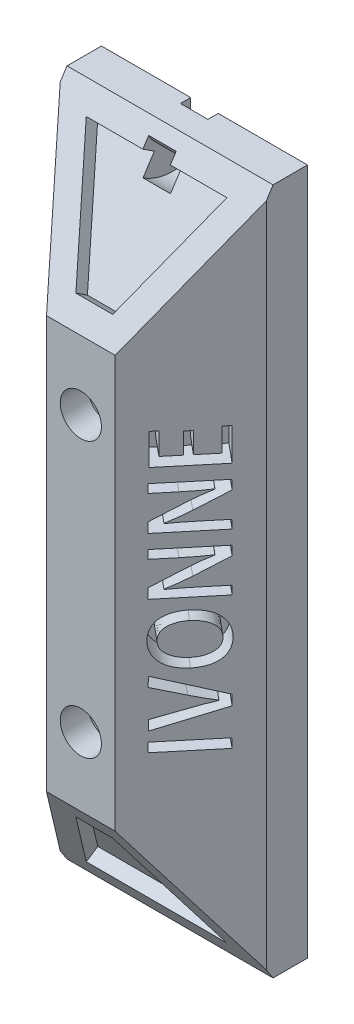
SolidWorks part; units mm, degrees
ref_plane "Alzado" through (0, 0, 0) normal (0, 0, 1) x (1, 0, 0)
ref_plane "Planta" through (0, 0, 0) normal (0, 1, 0) x (1, 0, 0)
ref_plane "Vista lateral" through (0, 0, 0) normal (1, 0, 0) x (0, 0, -1)
sketch "Croquis1" plane through (0, 0, 0) normal (0, 0, 1) x (1, 0, 0)
  line L0 (-7.5, 0) -> (7.5, 0)
  line L1 (7.5, 0) -> (7.5, 3)
  line L2 (7.5, 3) -> (2.5, 9)
  line L3 (2.5, 9) -> (-2.5, 9)
  line L4 (-2.5, 9) -> (-7.5, 3)
  line L5 (-7.5, 3) -> (-7.5, 0)
  line L6 (0, 0) -> (0, 9) construction
  point P4 (0, 0)
  dimension "D1" = 15
  dimension "D2" = 9
  dimension "D3" = 5
  dimension "D4" = 3
extrude "Saliente-Extruir1" add sketch "Croquis1" along normal blind 50
chamfer "Chaflán1" distance 10 angle 33 2 edges at (0, 9, 0) (0, 9, 50)
sketch "Croquis3" plane through (0, 24.6012, 15.9762) normal (0, 0.8387, 0.5446) x (1, 0, 0)
  line L0 (0, -28.6451) -> (0, -40.5687) construction
  line L1 (-2.5, -28.6451) -> (2.5, -28.6451) construction
  line L2 (7.5, -40.5687) -> (-7.5, -40.5687) construction
  line L3 (-5.1181, -38.7687) -> (5.1181, -38.7687)
  line L4 (5.1181, -38.7687) -> (1.3402, -30.4451)
  line L5 (1.3402, -30.4451) -> (-1.3402, -30.4451)
  line L6 (-1.3402, -30.4451) -> (-5.1181, -38.7687)
  line L7 (-7.5, -39.6615) -> (-2.5, -28.6451) construction
  line L8 (2.5, -28.6451) -> (7.5, -39.6615) construction
  line L9 (-3.2291, -34.6069) -> (-4.8682, -33.863) construction
  line L10 (1.0689, -30.4451) -> (1.0689, -28.6451) construction
  line L11 (-1.937, -38.7687) -> (-1.937, -40.5687) construction
  point P9 (0, -38.7687)
  dimension "D1" = 1.8
  dimension "D2" = 2.6805
extrude "Cortar-Extruir1" cut sketch "Croquis3" against normal blind 1
ref_plane "Plano1" through (0, 0, 25) normal (0, 0, 1) x (1, 0, 0)
mirror "Simetría1" about plane through (0, 0, 25) normal (0, 0, 1) of "Cortar-Extruir1"
sketch "Croquis4" plane through (0, 9, 0) normal (0, 1, 0) x (1, 0, 0)
  line L0 (-2.5, -25) -> (2.5, -25) construction
  line L1 (-2.5, -40) -> (-2.5, -10) construction
  line L2 (2.5, -40) -> (2.5, -10) construction
  line L3 (0, -35) -> (0, -15)
  circle A0 centre (0, -35) radius 1.5
  circle A1 centre (0, -15) radius 1.5
  point P10 (0, -25)
  dimension "D1" = 3
  dimension "D2" = 20
extrude "Huecos tornillos" cut sketch "Croquis4" against normal blind 2
sketch "Croquis5" plane through (5.9016, 4.918, 0) normal (0.7682, 0.6402, 0) x (0, 0, -1)
  line L0 (-44.6196, -0.7331) -> (-5.3804, -0.7331) construction
  line L3 (-49.2392, -2.4967) -> (-0.7608, -2.4967) construction
  text T0 "IVONNE" font "@Adobe Heiti Std R" height in points 14
extrude "PUEBLA-1" cut sketch "Croquis5" against normal blind 1.8
sketch "Croquis7" plane through (-5.9016, 4.918, 0) normal (-0.7682, 0.6402, 0) x (0, 0, 1)
  line L0 (5.3804, -0.7404) -> (44.6196, -0.7404) construction
  text T0 "PUEBLA" font "@Adobe Heiti Std R" height in points 14
extrude "PUEBLA-2" cut sketch "Croquis7" against normal blind 1.8
sketch "Croquis8" plane through (7.5, 0, 0) normal (1, 0, 0) x (0, 0, -1)
  line L0 (0, 0) -> (0, 2.5059) construction
  circle A0 centre (0, 1.253) radius 2
  circle A1 centre (0, 1.253) radius 4
  dimension "D1" = 2
  dimension "D2" = 4
extrude "ranura llavero" cut sketch "Croquis8" against normal blind 1 and the other way blind 1 from offset 7.5 offset against normal yes
sketch "Croquis10" plane through (0, 0, 0) normal (0, -1, 0) x (1, 0, 0)
  line L0 (-1, 2) -> (-1, 0)
  line L1 (-7.5, 0) -> (7.5, 0) construction
  line L2 (-1, 0) -> (1, 0)
  line L3 (1, 0) -> (1, 2)
  line L4 (1, 2) -> (-1, 2)
  line L5 (1, 2) -> (-1, 2) construction
extrude "espacio llavero debajo" cut sketch "Croquis10" against normal blind 0.75
sketch "Croquis23" [suppressed] plane through (0, 0, 0) normal (0, -1, 0) x (1, 0, 0)
  line L9 (-4.8602, 5.453) -> (-4.533, 5.1217)
  line L88 (-4.0291, 5.2989) -> (-4.0291, 5.7833)
  line L89 (-4.0291, 5.7833) -> (0.1999, 5.7833)
  line L90 (4.523, 6.259) -> (4.5043, 6.6454)
  line L91 (4.5043, 6.6454) -> (-0.1776, 6.6613)
  line L92 (-0.1776, 6.6613) -> (-4.8602, 6.6773)
  line L93 (-4.8602, 6.6773) -> (-4.8602, 6.0616)
  line L94 (-4.8602, 6.0616) -> (-4.8602, 5.453)
  line L95 (-4.8602, 5.453) -> (-4.8602, 5.453)
  line L96 (-4.836, 5.4629) -> (-4.836, 5.463)
  line L97 (-4.674, 23.8444) -> (-0.8024, 23.8444)
  line L109 (4.5212, 25.4088) -> (4.5043, 25.7617)
  line L188 (4.5043, 25.7617) -> (4.1218, 25.7617)
  line L189 (4.1218, 25.7617) -> (3.7406, 25.7617)
  line L190 (3.7406, 25.7617) -> (3.687, 25.4418)
  line L191 (0.4454, 24.6873) -> (-2.1005, 24.666)
  line L192 (-2.1005, 24.666) -> (-2.1181, 25.2021)
  line L193 (-2.1181, 25.2021) -> (-2.1365, 25.7617)
  line L194 (-2.1365, 25.7617) -> (-2.5517, 25.7617)
  line L195 (-2.5517, 25.7617) -> (-2.9668, 25.7617)
  line L200 (-2.9668, 25.7617) -> (-2.9851, 25.2069)
  line L201 (-2.9851, 25.2069) -> (-3.0027, 24.6755)
  line L202 (-3.0027, 24.6755) -> (-3.8264, 24.6755)
  line L203 (-3.8264, 24.6755) -> (-4.674, 24.6755)
  line L204 (-4.674, 24.6755) -> (-4.674, 24.26)
  line L205 (-4.674, 24.26) -> (-4.674, 23.8444)
  line L206 (-4.674, 30.3613) -> (-0.7631, 30.3613)
  line L207 (4.5296, 31.9094) -> (4.5361, 32.2475)
  line L208 (4.5361, 32.2475) -> (4.1284, 32.2475)
  line L209 (4.1284, 32.2475) -> (3.7223, 32.2475)
  line L210 (3.7223, 32.2475) -> (3.6813, 31.9377)
  line L211 (0.4739, 31.2054) -> (-2.1051, 31.1851)
  line L212 (-2.1051, 31.1851) -> (-2.1051, 31.7042)
  line L213 (-2.9983, 31.6692) -> (-2.9983, 31.1924)
  line L214 (-2.9983, 31.1924) -> (-3.824, 31.1924)
  line L215 (-3.824, 31.1924) -> (-4.674, 31.1924)
  line L216 (-4.674, 31.1924) -> (-4.674, 30.7592)
  line L217 (-4.674, 30.7592) -> (-4.674, 30.3613)
  line L218 (4.4171, 16.1181) -> (4.4283, 16.1365)
  line L219 (4.4283, 16.1365) -> (4.4261, 16.1365)
  line L220 (4.5314, 16.5641) -> (4.5272, 16.8123)
  line L221 (4.5272, 16.8123) -> (4.5346, 17.067)
  line L222 (2.6505, 18.7792) -> (2.2153, 18.7792)
  line L223 (2.2153, 18.7792) -> (2.2153, 18.3723)
  line L224 (2.2153, 18.3723) -> (2.2153, 17.9665)
  line L225 (2.2153, 17.9665) -> (2.6451, 17.9231)
  line L226 (2.3822, 16.1838) -> (1.7072, 16.1616)
  line L227 (1.7072, 16.1616) -> (1.0601, 17.4636)
  line L228 (1.0601, 17.4636) -> (0.4063, 18.7792)
  line L229 (0.4063, 18.7792) -> (-0.5423, 18.7792)
  line L230 (4.5312, 38.1525) -> (4.5317, 38.8949)
  line L231 (2.7866, 40.1384) -> (2.3089, 40.1615)
  line L232 (2.3089, 40.1615) -> (2.29, 39.7304)
  line L233 (2.29, 39.7304) -> (2.2711, 39.2988)
  line L234 (2.2711, 39.2988) -> (2.5008, 39.2988)
  line L235 (-1.1845, 39.2674) -> (-0.7092, 39.3356)
  line L236 (-0.7092, 39.3356) -> (-0.6904, 39.7237)
  line L237 (4.5296, 42.0359) -> (4.5305, 42.6933)
  line L238 (4.5305, 42.6933) -> (4.5332, 42.8981)
  line L239 (4.4549, 44.1716) -> (4.4547, 44.1716)
  line L240 (4.4547, 44.1716) -> (4.4546, 44.1716)
  line L241 (4.4546, 44.1716) -> (-1.4639, 44.172)
  line L242 (-1.4639, 44.172) -> (-1.5989, 44.17)
  line L243 (4.5359, 8.1299) -> (4.5359, 8.5506)
  line L244 (4.5359, 8.5506) -> (1.5603, 8.5506)
  line L245 (1.5138, 10.3141) -> (4.5044, 10.3453)
  line L246 (4.5044, 10.3453) -> (4.5233, 10.7789)
  line L247 (4.5233, 10.7789) -> (4.5423, 11.2138)
  line L248 (4.5423, 11.2138) -> (1.4389, 11.195)
  line L249 (4.5359, 19.9855) -> (4.5359, 20.3884)
  line L250 (4.5359, 20.3884) -> (1.5603, 20.4062)
  line L251 (1.532, 22.156) -> (4.542, 22.1744)
  line L252 (4.542, 22.1744) -> (4.5232, 22.6031)
  line L253 (4.5232, 22.6031) -> (4.5044, 23.0307)
  line L254 (4.5044, 23.0307) -> (1.731, 23.0478)
  line L255 (4.5336, 33.8803) -> (4.5319, 34.1285)
  line L256 (4.5319, 34.5628) -> (4.5339, 34.7986)
  line L257 (2.7711, 36.0835) -> (2.2153, 36.1114)
  line L258 (2.2153, 36.1114) -> (2.2153, 35.7)
  line L259 (2.2153, 35.7) -> (2.2153, 35.2909)
  line L260 (2.2153, 35.2909) -> (2.6777, 35.2243)
  line L261 (2.2806, 33.4892) -> (1.6897, 33.4888)
  line L262 (1.6897, 33.4888) -> (1.0517, 34.7913)
  line L263 (1.0517, 34.7913) -> (0.407, 36.1075)
  line L264 (0.407, 36.1075) -> (-0.6574, 36.0846)
  line L265 (4.4622, 26.985) -> (4.4721, 27.003)
  line L266 (4.4721, 27.003) -> (4.4692, 27.003)
  line L267 (4.5297, 27.3634) -> (4.5273, 27.6117)
  line L268 (4.5117, 20.3643) -> (4.5117, 19.9855)
  line L269 (-3.0334, 21.2807) -> (-3.0334, 21.2808)
  line L270 (4.2314, 12.8087) -> (4.5359, 12.8713)
  line L271 (4.5359, 12.8713) -> (4.5359, 13.2433)
  line L272 (4.5359, 13.2433) -> (4.5359, 13.6152)
  line L273 (4.5359, 13.6152) -> (4.2315, 13.6803)
  line L274 (-2.9983, 11.8993) -> (-2.9983, 11.8993)
  line L275 (-2.9741, 11.8994) -> (-2.9741, 11.8993)
  line L276 (-0.4884, 35.2633) -> (-0.2015, 35.2645)
  line L277 (-0.2015, 35.2645) -> (0.2301, 34.4032)
  line L278 (-0.5815, 17.9469) -> (-0.2015, 17.9482)
  line L279 (-0.2015, 17.9482) -> (0.2301, 17.0868)
  spline S0 degree 3 poles (-4.533, 5.1217) (-4.5035, 5.0924) (-4.4466, 5.0359) (-4.3621, 4.9585) (-4.2952, 4.9011) (-4.2461, 4.8622) (-4.2142, 4.8383) (-4.1858, 4.819) (-4.1616, 4.8039) (-4.1409, 4.7933) (-4.121, 4.7889) (-4.1018, 4.7931) (-4.0852, 4.8052) (-4.072, 4.8236) (-4.0618, 4.8479) (-4.0534, 4.878) (-4.0434, 4.9319) (-4.0351, 5.0186) (-4.0298, 5.1475) (-4.0294, 5.2446) (-4.0291, 5.2989) knots 0 0 0 0 0.115946 0.224108 0.320001 0.361964 0.399248 0.431375 0.457779 0.478836 0.49618 0.513638 0.53192 0.552362 0.57622 0.605016 0.63966 0.729037 0.848151 1 1 1 1
  spline S1 degree 3 poles (0.1999, 5.7833) (0.5752, 5.7836) (1.2893, 5.7842) (2.2921, 5.7885) (3.0408, 5.7942) (3.554, 5.8) (3.8624, 5.8046) (4.0838, 5.8089) (4.2304, 5.8127) (4.3159, 5.8154) (4.3766, 5.8178) (4.4164, 5.8198) (4.4395, 5.8213) (4.456, 5.8225) (4.4669, 5.8236) (4.4735, 5.8244) (4.4782, 5.8251) (4.4816, 5.8256) (4.4838, 5.8261) (4.4859, 5.8267) (4.4881, 5.8271) (4.4909, 5.8283) (4.4946, 5.8316) (4.4987, 5.8369) (4.5023, 5.8442) (4.5052, 5.8525) (4.508, 5.8619) (4.5105, 5.8725) (4.5137, 5.8891) (4.5171, 5.913) (4.5205, 5.945) (4.5242, 5.9955) (4.5267, 6.0669) (4.5269, 6.16) (4.5243, 6.2252) (4.523, 6.259) knots 0 0 0 0 0.238071 0.453081 0.636227 0.713099 0.778704 0.831946 0.853588 0.871732 0.886247 0.892105 0.897014 0.900968 0.902584 0.903969 0.905139 0.905647 0.906119 0.906572 0.907018 0.907574 0.908473 0.910111 0.911781 0.913613 0.915677 0.917986 0.920548 0.926427 0.933254 0.940954 0.958598 0.978554 1 1 1 1
  spline S2 degree 3 poles (-0.8024, 23.8444) (0.0364, 23.845) (1.2812, 23.8458) (2.6838, 23.8589) (3.3332, 23.9062) (3.6318, 24.0192) (3.8297, 24.1167) (4.0103, 24.2298) (4.1539, 24.3836) (4.2826, 24.5543) (4.3964, 24.751) (4.4791, 24.9573) (4.5261, 25.1817) (4.5229, 25.3309) (4.5212, 25.4088) knots 0 0 0 0 0.404979 0.601004 0.68012 0.716413 0.754468 0.786796 0.818638 0.855447 0.890061 0.928098 0.96245 1 1 1 1
  spline S3 degree 3 poles (3.687, 25.4418) (3.6816, 25.4132) (3.6707, 25.3557) (3.6478, 25.2719) (3.6218, 25.1926) (3.5934, 25.1222) (3.5653, 25.0647) (3.5236, 25.003) (3.4448, 24.942) (3.339, 24.8707) (3.1644, 24.7708) (2.735, 24.7213) (1.8158, 24.7009) (0.9952, 24.6927) (0.4454, 24.6873) knots 0 0 0 0 0.024157 0.048552 0.07202 0.093418 0.111517 0.125098 0.154806 0.193069 0.231545 0.320142 0.544436 1 1 1 1
  spline S4 degree 3 poles (-0.7631, 30.3613) (0.0842, 30.3625) (1.3391, 30.3642) (2.7501, 30.3736) (3.4028, 30.4249) (3.7044, 30.5394) (3.9156, 30.6737) (4.0957, 30.8424) (4.2538, 31.0255) (4.3736, 31.1956) (4.461, 31.359) (4.4933, 31.5323) (4.5202, 31.7137) (4.5264, 31.8444) (4.5296, 31.9094) knots 0 0 0 0 0.411894 0.610137 0.688322 0.727681 0.765748 0.809404 0.847223 0.883282 0.91065 0.936429 0.968386 1 1 1 1
  spline S5 degree 3 poles (3.6813, 31.9377) (3.6706, 31.8803) (3.6498, 31.769) (3.5941, 31.6229) (3.5229, 31.5045) (3.4263, 31.4234) (3.3292, 31.3548) (3.2486, 31.3019) (3.1737, 31.283) (3.0996, 31.2733) (2.993, 31.2629) (2.8535, 31.2538) (2.6805, 31.2452) (2.3804, 31.234) (1.9152, 31.2226) (1.2449, 31.2122) (0.748, 31.2078) (0.4739, 31.2054) knots 0 0 0 0 0.048816 0.094618 0.130448 0.1631 0.199111 0.230695 0.242519 0.263434 0.293324 0.332245 0.380521 0.438382 0.583791 0.770368 1 1 1 1
  spline S6 degree 3 poles (-2.1051, 31.7042) (-2.1054, 31.7614) (-2.1059, 31.8642) (-2.1112, 32.0015) (-2.1194, 32.0949) (-2.1292, 32.1535) (-2.1373, 32.1867) (-2.147, 32.2136) (-2.1591, 32.2343) (-2.1746, 32.2495) (-2.2133, 32.2593) (-2.2886, 32.2572) (-2.4076, 32.2657) (-2.5266, 32.2699) (-2.628, 32.2715) (-2.7021, 32.2682) (-2.7704, 32.2617) (-2.8299, 32.2528) (-2.8779, 32.2413) (-2.912, 32.2276) (-2.9319, 32.208) (-2.9441, 32.1868) (-2.9546, 32.1605) (-2.9639, 32.1286) (-2.972, 32.0911) (-2.9819, 32.0296) (-2.9909, 31.9382) (-2.9973, 31.8113) (-2.9979, 31.7191) (-2.9983, 31.6692) knots 0 0 0 0 0.091635 0.164427 0.219802 0.241473 0.259534 0.274426 0.286968 0.297829 0.307914 0.349599 0.41806 0.498792 0.540099 0.5802 0.617395 0.649878 0.676396 0.696464 0.707563 0.720297 0.735302 0.752916 0.773355 0.796731 0.852482 0.920263 1 1 1 1
  spline S7 degree 3 poles (-3.0603, 16.9878) (-3.0592, 16.8906) (-3.0571, 16.714) (-3.0034, 16.4571) (-2.9082, 16.2368) (-2.7861, 16.0339) (-2.646, 15.8615) (-2.4876, 15.7152) (-2.3031, 15.6034) (-2.112, 15.5035) (-1.928, 15.4235) (-1.7429, 15.371) (-1.5202, 15.3421) (-1.1955, 15.3246) (-0.7176, 15.3149) (-0.0355, 15.3107) (0.8099, 15.3103) (1.6577, 15.3106) (2.35, 15.3143) (2.8241, 15.3243) (3.1397, 15.3428) (3.3562, 15.3766) (3.5388, 15.4356) (3.7224, 15.5184) (3.9078, 15.6209) (4.0737, 15.7321) (4.2067, 15.86) (4.3236, 15.9848) (4.3879, 16.0764) (4.4171, 16.1181) knots 0 0 0 0 0.033474 0.060852 0.089936 0.115893 0.14239 0.166392 0.189902 0.216553 0.240885 0.259001 0.282767 0.318191 0.371217 0.447755 0.553655 0.663009 0.740387 0.792636 0.826675 0.849467 0.868016 0.892741 0.918872 0.941121 0.961395 0.982429 1 1 1 1
  spline S8 degree 3 poles (4.4261, 16.1365) (4.446, 16.1796) (4.4876, 16.2695) (4.5233, 16.4145) (4.5287, 16.5151) (4.5314, 16.5641) knots 0 0 0 0 0.319971 0.669084 1 1 1 1
  spline S9 degree 3 poles (4.5346, 17.067) (4.5257, 17.1146) (4.5132, 17.1814) (4.5534, 17.3232) (4.5282, 17.3196) (4.5274, 17.3195) knots 0 0 0 0 0.705879 0.991017 1 1 1 1
  spline S10 degree 3 poles (4.5274, 17.3195) (4.5283, 17.3218) (4.53, 17.3266) (4.5274, 17.3345) (4.5276, 17.3429) (4.5278, 17.3516) (4.5246, 17.3611) (4.5249, 17.3808) (4.527, 17.413) (4.5281, 17.46) (4.5313, 17.5541) (4.525, 17.6901) (4.4731, 17.861) (4.3851, 18.0164) (4.262, 18.1622) (4.122, 18.2971) (3.9642, 18.4237) (3.7818, 18.5253) (3.5898, 18.6149) (3.3853, 18.6937) (3.1574, 18.7384) (2.9109, 18.7706) (2.7363, 18.7764) (2.6505, 18.7792) knots 0 0 0 0 0.002681 0.00556 0.008912 0.012023 0.015169 0.019893 0.033833 0.051275 0.072316 0.138944 0.201935 0.269662 0.336675 0.414045 0.48641 0.561583 0.646172 0.722874 0.805208 0.904392 1 1 1 1
  spline S11 degree 3 poles (2.6451, 17.9231) (2.7272, 17.9118) (2.8918, 17.8891) (3.1169, 17.8325) (3.3122, 17.7682) (3.4641, 17.6753) (3.5856, 17.5802) (3.6871, 17.4779) (3.7402, 17.3474) (3.7778, 17.2063) (3.7974, 17.0489) (3.7871, 16.8931) (3.7473, 16.7462) (3.6775, 16.6182) (3.5705, 16.5102) (3.4468, 16.4118) (3.2909, 16.3131) (3.0777, 16.2384) (2.7659, 16.1986) (2.5258, 16.1893) (2.3822, 16.1838) knots 0 0 0 0 0.071677 0.143744 0.200762 0.248843 0.296831 0.3347 0.371627 0.416944 0.461259 0.508217 0.551219 0.592125 0.632837 0.681882 0.728922 0.791897 0.875562 1 1 1 1
  spline S12 degree 3 poles (-0.5423, 18.7792) (-0.7496, 18.7789) (-1.0929, 18.7784) (-1.5515, 18.7454) (-1.8915, 18.6584) (-2.1752, 18.5603) (-2.4174, 18.4174) (-2.6114, 18.2394) (-2.7798, 18.0496) (-2.9052, 17.8654) (-2.9928, 17.6787) (-3.027, 17.4694) (-3.0539, 17.2394) (-3.0582, 17.0721) (-3.0603, 16.9878) knots 0 0 0 0 0.174123 0.288318 0.384596 0.467994 0.539585 0.618857 0.688095 0.752242 0.805463 0.859622 0.92923 1 1 1 1
  spline S13 degree 3 poles (-3.0603, 38.4494) (-3.059, 38.3492) (-3.0566, 38.1697) (-3.0154, 37.9199) (-2.9392, 37.716) (-2.8282, 37.5373) (-2.7018, 37.377) (-2.5565, 37.2253) (-2.379, 37.1024) (-2.1875, 36.9935) (-2.0009, 36.9088) (-1.8151, 36.8547) (-1.5986, 36.8226) (-1.2902, 36.8016) (-0.8432, 36.787) (-0.2106, 36.7763) (0.5, 36.7683) (1.1979, 36.7628) (1.775, 36.7629) (2.2597, 36.7675) (2.6462, 36.7765) (2.9287, 36.789) (3.1602, 36.8103) (3.378, 36.8694) (3.6104, 36.9453) (3.837, 37.0362) (4.0374, 37.1544) (4.2128, 37.2934) (4.3565, 37.4551) (4.4648, 37.6228) (4.5286, 37.8098) (4.53, 37.9558) (4.5292, 38.0584) (4.5318, 38.1087) (4.5314, 38.1391) (4.5312, 38.1525) knots 0 0 0 0 0.032312 0.057867 0.081261 0.101995 0.125474 0.147082 0.16943 0.194817 0.218156 0.23532 0.257082 0.288606 0.335005 0.401363 0.49271 0.564243 0.626512 0.678864 0.720629 0.751212 0.770106 0.795465 0.823732 0.849056 0.874027 0.898529 0.920936 0.943537 0.962538 0.983769 0.990193 0.995664 1 1 1 1
  spline S14 degree 3 poles (4.5317, 38.8949) (4.5297, 38.9432) (4.5255, 39.0422) (4.4951, 39.1818) (4.4493, 39.3156) (4.3635, 39.4362) (4.2601, 39.5583) (4.1346, 39.6856) (3.9732, 39.7995) (3.7887, 39.9039) (3.5811, 40.0011) (3.3387, 40.0645) (3.0713, 40.1147) (2.8806, 40.1306) (2.7866, 40.1384) knots 0 0 0 0 0.061411 0.125783 0.181154 0.239773 0.312427 0.384794 0.466326 0.562609 0.654348 0.756746 0.880106 1 1 1 1
  spline S15 degree 3 poles (2.5008, 39.2988) (2.5518, 39.2963) (2.6683, 39.2905) (2.8492, 39.2649) (3.0492, 39.231) (3.2443, 39.1773) (3.4239, 39.0868) (3.55, 38.9797) (3.6392, 38.8858) (3.6966, 38.8142) (3.7351, 38.7416) (3.7567, 38.6604) (3.766, 38.5634) (3.7675, 38.4538) (3.7659, 38.3445) (3.7569, 38.2491) (3.737, 38.1696) (3.7026, 38.0996) (3.6514, 38.0329) (3.5742, 37.9494) (3.455, 37.8584) (3.3009, 37.7758) (3.1431, 37.7125) (2.9535, 37.6922) (2.7054, 37.6761) (2.3542, 37.6635) (1.9052, 37.6542) (1.3618, 37.6485) (0.9685, 37.6479) (0.7568, 37.6476) knots 0 0 0 0 0.029724 0.067928 0.106261 0.147892 0.185256 0.222345 0.243592 0.260669 0.275659 0.291044 0.309252 0.332292 0.354865 0.372865 0.387994 0.402303 0.417948 0.436785 0.46844 0.504651 0.538577 0.566473 0.615118 0.683574 0.770996 0.876718 1 1 1 1
  spline S16 degree 3 poles (0.7568, 37.6476) (0.5542, 37.648) (0.1733, 37.6487) (-0.3578, 37.6547) (-0.7498, 37.6627) (-1.0187, 37.6712) (-1.1837, 37.678) (-1.3222, 37.6853) (-1.4329, 37.6935) (-1.514, 37.7015) (-1.608, 37.7178) (-1.7233, 37.7694) (-1.8631, 37.8453) (-1.994, 37.9378) (-2.0953, 38.0536) (-2.1695, 38.1826) (-2.2133, 38.3222) (-2.2167, 38.4691) (-2.1967, 38.6172) (-2.1538, 38.764) (-2.0773, 38.8967) (-1.9767, 39.009) (-1.8473, 39.1045) (-1.6645, 39.164) (-1.4419, 39.2239) (-1.2723, 39.2526) (-1.1845, 39.2674) knots 0 0 0 0 0.125456 0.235833 0.328893 0.368228 0.402393 0.431109 0.454134 0.471104 0.481577 0.513065 0.548443 0.580266 0.61168 0.642861 0.67189 0.701201 0.733032 0.764252 0.795252 0.827003 0.857063 0.893601 0.944968 1 1 1 1
  spline S17 degree 3 poles (-0.6904, 39.7237) (-0.6885, 39.7673) (-0.6852, 39.8448) (-0.6859, 39.9481) (-0.6921, 40.018) (-0.702, 40.0621) (-0.7111, 40.0881) (-0.7228, 40.1099) (-0.7373, 40.1275) (-0.7546, 40.1409) (-0.7736, 40.1505) (-0.7958, 40.1559) (-0.8224, 40.1588) (-0.8556, 40.1606) (-0.8953, 40.1614) (-0.9408, 40.1612) (-1.0113, 40.1594) (-1.109, 40.1543) (-1.2344, 40.1446) (-1.4149, 40.1265) (-1.6393, 40.0932) (-1.8793, 40.0441) (-2.0772, 39.99) (-2.2356, 39.908) (-2.3821, 39.8215) (-2.5325, 39.7241) (-2.668, 39.5883) (-2.7935, 39.4248) (-2.9115, 39.2275) (-3.0066, 39.0083) (-3.0584, 38.7404) (-3.0596, 38.5542) (-3.0603, 38.4494) knots 0 0 0 0 0.035122 0.062414 0.083104 0.091437 0.098721 0.105218 0.111217 0.116972 0.122715 0.128179 0.1353 0.144224 0.154923 0.167194 0.180865 0.211692 0.245926 0.282071 0.357678 0.428264 0.479343 0.522065 0.571166 0.616524 0.665684 0.72466 0.782074 0.850364 0.915796 1 1 1 1
  spline S18 degree 3 poles (-3.0594, 42.5694) (-3.0576, 42.4852) (-3.0541, 42.3197) (-3.0303, 42.0941) (-3.0022, 41.8938) (-2.922, 41.7183) (-2.8151, 41.5483) (-2.6805, 41.3746) (-2.5077, 41.2209) (-2.3186, 41.0854) (-2.1099, 40.9664) (-1.8584, 40.8926) (-1.5728, 40.8284) (-1.2054, 40.7721) (-0.6925, 40.7527) (-0.0064, 40.7327) (0.7995, 40.7254) (1.6042, 40.7326) (2.2873, 40.7524) (2.8076, 40.7763) (3.1821, 40.834) (3.4927, 40.9177) (3.7663, 41.0339) (4.0063, 41.1678) (4.2041, 41.3167) (4.3538, 41.4857) (4.4645, 41.6564) (4.5288, 41.844) (4.5293, 41.9696) (4.5296, 42.0359) knots 0 0 0 0 0.027266 0.053609 0.073606 0.09236 0.11553 0.138688 0.163281 0.190166 0.214047 0.240676 0.274654 0.308989 0.360916 0.440801 0.53149 0.622039 0.701565 0.753012 0.790662 0.824143 0.856969 0.886735 0.913056 0.936751 0.959543 0.978657 1 1 1 1
  spline S19 degree 3 poles (4.5332, 42.8981) (4.5315, 42.9408) (4.5281, 43.0296) (4.502, 43.159) (4.4619, 43.2686) (4.4171, 43.3476) (4.3922, 43.3995) (4.377, 43.4297) (4.3777, 43.4429) (4.3784, 43.4459) (4.3794, 43.448) (4.3809, 43.4498) (4.3831, 43.4513) (4.388, 43.4536) (4.3973, 43.4556) (4.4117, 43.4571) (4.4295, 43.457) (4.4489, 43.4584) (4.4676, 43.4648) (4.484, 43.4761) (4.4975, 43.4925) (4.5082, 43.5134) (4.5201, 43.5505) (4.5332, 43.6107) (4.5453, 43.702) (4.5483, 43.7876) (4.5472, 43.8769) (4.5467, 43.9571) (4.5452, 44.0213) (4.5444, 44.0515) knots 0 0 0 0 0.100353 0.2088 0.308919 0.373812 0.421046 0.446662 0.449751 0.451996 0.453714 0.455343 0.457337 0.460018 0.468006 0.479463 0.494193 0.50981 0.524883 0.540092 0.556237 0.574227 0.594938 0.647797 0.718903 0.811186 0.849077 0.928925 1 1 1 1
  spline S20 degree 3 poles (4.5444, 44.0515) (4.5467, 44.075) (4.5503, 44.1131) (4.5141, 44.1655) (4.477, 44.1693) (4.4549, 44.1716) knots 0 0 0 0 0.393584 0.638206 1 1 1 1
  spline S21 degree 3 poles (-1.5989, 44.17) (-1.6367, 44.1655) (-1.7528, 44.1516) (-1.9347, 44.1228) (-2.1284, 44.0786) (-2.2781, 43.9855) (-2.4144, 43.9003) (-2.5578, 43.806) (-2.6894, 43.6747) (-2.8091, 43.5129) (-2.9204, 43.3182) (-3.0051, 43.0996) (-3.0549, 42.8434) (-3.0578, 42.6659) (-3.0594, 42.5694) knots 0 0 0 0 0.047149 0.145043 0.229101 0.290416 0.362081 0.429042 0.502565 0.591199 0.678138 0.780108 0.880513 1 1 1 1
  spline S22 degree 3 poles (-3.0589, 9.4296) (-3.0571, 9.325) (-3.0539, 9.138) (-3.018, 8.8837) (-2.9517, 8.6824) (-2.852, 8.5145) (-2.7425, 8.3638) (-2.6168, 8.2204) (-2.4628, 8.1) (-2.2959, 7.9908) (-2.1117, 7.8904) (-1.8961, 7.8186) (-1.6565, 7.7568) (-1.4149, 7.7059) (-1.1319, 7.6893) (-0.7659, 7.6759) (-0.2654, 7.6642) (0.3393, 7.6546) (1.0181, 7.6483) (1.7314, 7.6459) (2.4316, 7.6472) (3.0726, 7.6508) (3.5517, 7.656) (3.8807, 7.6613) (4.0788, 7.6655) (4.2213, 7.6694) (4.316, 7.673) (4.3714, 7.6755) (4.4109, 7.6777) (4.437, 7.6796) (4.4523, 7.681) (4.4633, 7.6822) (4.4708, 7.6832) (4.4754, 7.684) (4.4794, 7.6847) (4.4831, 7.6854) (4.4872, 7.6865) (4.4915, 7.6906) (4.496, 7.6961) (4.4995, 7.7033) (4.5024, 7.7115) (4.5053, 7.7209) (4.508, 7.7316) (4.5116, 7.7485) (4.5157, 7.7728) (4.52, 7.8055) (4.5256, 7.8575) (4.5309, 7.931) (4.5351, 8.0273) (4.5356, 8.0949) (4.5359, 8.1299) knots 0 0 0 0 0.034827 0.062273 0.085234 0.10489 0.127041 0.147289 0.168155 0.191897 0.213731 0.237803 0.267335 0.296219 0.319841 0.361598 0.418283 0.486585 0.563087 0.644411 0.724194 0.796353 0.857925 0.883815 0.905948 0.923958 0.931303 0.937483 0.942456 0.944478 0.946187 0.947586 0.948171 0.948685 0.94916 0.94952 0.949927 0.95058 0.951428 0.952288 0.953241 0.954327 0.955551 0.956917 0.960072 0.963753 0.967916 0.977481 0.988325 1 1 1 1
  spline S23 degree 3 poles (1.5603, 8.5506) (1.1527, 8.5533) (0.4652, 8.5577) (-0.4022, 8.566) (-0.9695, 8.5796) (-1.32, 8.5994) (-1.5387, 8.6371) (-1.7003, 8.7044) (-1.8493, 8.789) (-1.9832, 8.8906) (-2.0937, 9) (-2.1521, 9.138) (-2.1896, 9.2932) (-2.2015, 9.4695) (-2.1951, 9.6408) (-2.1452, 9.7998) (-2.0516, 9.9183) (-1.9362, 10.021) (-1.8123, 10.1091) (-1.6241, 10.2242) (-1.1417, 10.2698) (-0.086, 10.2972) (0.8686, 10.3073) (1.5138, 10.3141) knots 0 0 0 0 0.145703 0.245761 0.310071 0.348513 0.371277 0.3889 0.410802 0.432331 0.449012 0.465553 0.485058 0.505979 0.528506 0.546036 0.564476 0.581663 0.601185 0.618859 0.659709 0.769985 1 1 1 1
  spline S24 degree 3 poles (1.4389, 11.195) (1.0135, 11.1924) (0.2958, 11.188) (-0.6105, 11.1795) (-1.206, 11.1661) (-1.5786, 11.1453) (-1.8167, 11.1062) (-2.0017, 11.0361) (-2.1838, 10.9517) (-2.3634, 10.8527) (-2.5298, 10.7517) (-2.6658, 10.6124) (-2.7901, 10.4486) (-2.9087, 10.2476) (-3.0081, 10.0232) (-3.0593, 9.7405) (-3.059, 9.5431) (-3.0589, 9.4296) knots 0 0 0 0 0.230937 0.389665 0.492079 0.554229 0.592257 0.622399 0.661294 0.701183 0.733829 0.766384 0.806088 0.845284 0.892951 0.938444 1 1 1 1
  spline S25 degree 3 poles (-3.0576, 21.2808) (-3.056, 21.1772) (-3.0532, 20.9912) (-3.0182, 20.7383) (-2.9534, 20.5371) (-2.8554, 20.3693) (-2.7481, 20.2183) (-2.6254, 20.0753) (-2.4773, 19.9549) (-2.3193, 19.846) (-2.1473, 19.7465) (-1.9473, 19.6748) (-1.7263, 19.6129) (-1.5414, 19.5698) (-1.394, 19.5536) (-1.2717, 19.546) (-1.1095, 19.5382) (-0.91, 19.531) (-0.676, 19.5243) (-0.3038, 19.5159) (0.2254, 19.5079) (0.9235, 19.5016) (1.4164, 19.5008) (1.674, 19.5003) knots 0 0 0 0 0.054064 0.097009 0.132845 0.163519 0.198027 0.2295 0.261482 0.297292 0.329695 0.364843 0.407751 0.449577 0.46366 0.485103 0.513508 0.548417 0.589304 0.63566 0.742735 0.865548 1 1 1 1
  spline S26 degree 3 poles (1.674, 19.5003) (1.919, 19.5005) (2.3855, 19.5009) (3.041, 19.505) (3.531, 19.5102) (3.8674, 19.5157) (4.0701, 19.5199) (4.2158, 19.5239) (4.3124, 19.5275) (4.3691, 19.53) (4.4094, 19.5323) (4.4361, 19.5342) (4.4517, 19.5356) (4.4629, 19.5368) (4.4705, 19.5378) (4.4752, 19.5386) (4.4786, 19.5393) (4.4812, 19.5399) (4.4829, 19.5403) (4.4847, 19.5409) (4.4866, 19.5416) (4.4888, 19.5428) (4.4921, 19.5457) (4.496, 19.5507) (4.4995, 19.5579) (4.5024, 19.5661) (4.5053, 19.5755) (4.508, 19.5862) (4.5116, 19.6031) (4.5157, 19.6275) (4.52, 19.6603) (4.5256, 19.7124) (4.5309, 19.7861) (4.5351, 19.8826) (4.5356, 19.9504) (4.5359, 19.9855) knots 0 0 0 0 0.225079 0.428626 0.602291 0.675308 0.737728 0.788511 0.809212 0.826622 0.840628 0.846322 0.851134 0.855067 0.856704 0.858139 0.859399 0.859973 0.860527 0.861084 0.86167 0.862382 0.863382 0.86572 0.868092 0.870721 0.873723 0.87711 0.880888 0.889603 0.899775 0.911281 0.937726 0.967714 1 1 1 1
  spline S27 degree 3 poles (1.5603, 20.4062) (1.1513, 20.4087) (0.4621, 20.4129) (-0.4068, 20.4209) (-0.9738, 20.4343) (-1.3235, 20.4541) (-1.5419, 20.4925) (-1.7066, 20.5621) (-1.8608, 20.6486) (-2.0015, 20.7617) (-2.1078, 20.8864) (-2.1703, 21.0232) (-2.2123, 21.1524) (-2.236, 21.2805) (-2.213, 21.4078) (-2.1724, 21.5348) (-2.1127, 21.6676) (-2.008, 21.7878) (-1.8791, 21.9009) (-1.7583, 21.981) (-1.6646, 22.0296) (-1.5989, 22.0587) (-1.5205, 22.0814) (-1.419, 22.0991) (-1.2831, 22.113) (-1.0008, 22.1297) (-0.4776, 22.1408) (0.4066, 22.1493) (1.1117, 22.1535) (1.532, 22.156) knots 0 0 0 0 0.145931 0.245942 0.310054 0.348273 0.370922 0.388672 0.411816 0.433817 0.452785 0.469667 0.487066 0.501352 0.51553 0.532601 0.549005 0.567033 0.588919 0.610137 0.6185 0.626575 0.635758 0.647523 0.663303 0.684478 0.748402 0.850016 1 1 1 1
  spline S28 degree 3 poles (1.731, 23.0478) (1.4582, 23.0492) (0.9461, 23.0516) (0.2315, 23.05) (-0.3724, 23.0444) (-0.8548, 23.0347) (-1.2052, 23.0221) (-1.4793, 23.0019) (-1.716, 22.952) (-1.9452, 22.8935) (-2.147, 22.8288) (-2.3165, 22.7324) (-2.4725, 22.6237) (-2.6206, 22.4995) (-2.745, 22.3517) (-2.8542, 22.1967) (-2.9532, 22.0264) (-3.0181, 21.824) (-3.0532, 21.5706) (-3.056, 21.3845) (-3.0576, 21.2808) knots 0 0 0 0 0.140802 0.264407 0.36896 0.452576 0.513486 0.550045 0.594281 0.638056 0.672321 0.703208 0.738258 0.770479 0.802666 0.837626 0.868367 0.903941 0.946526 1 1 1 1
  spline S29 degree 3 poles (-3.0562, 34.4798) (-3.0564, 34.4545) (-3.0567, 34.4022) (-3.055, 34.3209) (-3.0482, 34.1531) (-3.0378, 33.9305) (-2.9696, 33.6557) (-2.8464, 33.4377) (-2.7015, 33.2354) (-2.5231, 33.0645) (-2.3214, 32.9231) (-2.0975, 32.8101) (-1.8752, 32.7209) (-1.6692, 32.6539) (-1.4477, 32.6323) (-1.1721, 32.619) (-0.7878, 32.6097) (-0.2965, 32.6049) (0.3002, 32.6049) (1.2312, 32.6111) (2.211, 32.6267) (3.07, 32.6409) (3.496, 32.7115) (3.7228, 32.8236) (3.8977, 32.9249) (4.0614, 33.0394) (4.2001, 33.1698) (4.3189, 33.2997) (4.4214, 33.4282) (4.4824, 33.5722) (4.5233, 33.7224) (4.5303, 33.8288) (4.5336, 33.8803) knots 0 0 0 0 0.008121 0.016805 0.026109 0.062082 0.08821 0.116156 0.141916 0.16794 0.195045 0.220763 0.248282 0.272016 0.289944 0.319514 0.3607 0.413373 0.477319 0.552342 0.712412 0.791883 0.828643 0.849441 0.872672 0.893623 0.91341 0.933639 0.950244 0.965831 0.983479 1 1 1 1
  spline S30 degree 3 poles (4.5319, 34.1285) (4.5315, 34.1583) (4.5301, 34.2501) (4.5284, 34.3949) (4.5308, 34.5098) (4.5319, 34.5628) knots 0 0 0 0 0.205911 0.634017 1 1 1 1
  spline S31 degree 3 poles (4.5339, 34.7986) (4.5315, 34.8466) (4.5267, 34.9446) (4.4966, 35.0821) (4.451, 35.2129) (4.3674, 35.3317) (4.268, 35.4547) (4.1478, 35.5852) (3.9946, 35.7062) (3.8199, 35.8191) (3.6195, 35.9275) (3.3839, 36.0086) (3.0952, 36.0622) (2.8858, 36.076) (2.7711, 36.0835) knots 0 0 0 0 0.060044 0.122438 0.175579 0.231982 0.302762 0.373725 0.453281 0.546195 0.633738 0.737656 0.856274 1 1 1 1
  spline S32 degree 3 poles (2.6777, 35.2243) (2.7645, 35.2094) (2.9354, 35.1802) (3.1651, 35.1204) (3.3628, 35.055) (3.518, 34.9642) (3.641, 34.8301) (3.7236, 34.6596) (3.7978, 34.492) (3.8187, 34.3161) (3.7795, 34.1629) (3.7146, 34.014) (3.6282, 33.8842) (3.5238, 33.7668) (3.3918, 33.6803) (3.2536, 33.607) (3.1292, 33.5554) (3.0146, 33.5339) (2.9023, 33.5197) (2.7647, 33.5071) (2.6102, 33.4975) (2.447, 33.4907) (2.3361, 33.4897) (2.2806, 33.4892) knots 0 0 0 0 0.074712 0.147018 0.201256 0.250924 0.297797 0.353141 0.410966 0.452536 0.500652 0.542992 0.590098 0.632408 0.675292 0.722973 0.765327 0.788762 0.821584 0.861421 0.905935 0.952885 1 1 1 1
  spline S33 degree 3 poles (-0.6574, 36.0846) (-0.8012, 36.0815) (-1.0483, 36.0761) (-1.3696, 36.0643) (-1.6043, 36.0452) (-1.7871, 36.0112) (-1.9494, 35.9543) (-2.1302, 35.8746) (-2.3309, 35.7687) (-2.5224, 35.6412) (-2.6813, 35.5089) (-2.7907, 35.3514) (-2.887, 35.189) (-2.9668, 35.021) (-3.0192, 34.8519) (-3.0496, 34.6728) (-3.0539, 34.5471) (-3.0562, 34.4798) knots 0 0 0 0 0.131623 0.226077 0.294162 0.346923 0.395592 0.451109 0.527649 0.602726 0.661589 0.715309 0.777031 0.834393 0.88499 0.93849 1 1 1 1
  spline S34 degree 3 poles (-3.0507, 27.7015) (-3.0457, 27.5935) (-3.037, 27.4054) (-2.9681, 27.1368) (-2.8466, 26.9208) (-2.7026, 26.7205) (-2.5281, 26.5516) (-2.3308, 26.4112) (-2.1076, 26.3012) (-1.8804, 26.2132) (-1.668, 26.1478) (-1.4442, 26.1245) (-1.1753, 26.1087) (-0.8096, 26.0957) (-0.3541, 26.086) (0.1846, 26.08) (0.7746, 26.0782) (1.3636, 26.08) (1.8987, 26.0859) (2.3514, 26.0955) (2.7136, 26.1084) (2.9777, 26.1233) (3.1908, 26.1465) (3.3853, 26.2043) (3.5896, 26.2742) (3.7825, 26.3551) (3.9518, 26.4565) (4.1014, 26.563) (4.2271, 26.6737) (4.3208, 26.7872) (4.4003, 26.887) (4.4434, 26.9553) (4.4622, 26.985) knots 0 0 0 0 0.037258 0.064959 0.094819 0.122278 0.149997 0.17825 0.205587 0.235696 0.262471 0.281961 0.313216 0.355586 0.408328 0.470618 0.541652 0.612143 0.674076 0.726526 0.76854 0.799261 0.817944 0.842381 0.869104 0.89258 0.914472 0.937106 0.955962 0.97212 0.987869 1 1 1 1
  spline S35 degree 3 poles (4.4692, 27.003) (4.4748, 27.0166) (4.4869, 27.046) (4.5004, 27.0951) (4.5126, 27.1537) (4.5221, 27.2203) (4.5288, 27.2917) (4.5294, 27.3397) (4.5297, 27.3634) knots 0 0 0 0 0.119929 0.25875 0.41495 0.608578 0.806594 1 1 1 1
  spline S36 degree 3 poles (4.5273, 27.6117) (4.5277, 27.6753) (4.5286, 27.8026) (4.5343, 27.9935) (4.5325, 28.1209) (4.5317, 28.1845) knots 0 0 0 0 0.333069 0.666775 1 1 1 1
  spline S37 degree 3 poles (4.5317, 28.1845) (4.5318, 28.2007) (4.5322, 28.236) (4.5298, 28.284) (4.5291, 28.3812) (4.5374, 28.521) (4.4627, 28.7092) (4.3463, 28.8809) (4.1938, 29.0536) (3.9962, 29.2036) (3.7591, 29.3371) (3.4884, 29.4509) (3.1805, 29.5332) (2.807, 29.591) (2.2873, 29.6147) (1.6042, 29.6346) (0.7995, 29.6417) (-0.0064, 29.6345) (-0.6925, 29.6145) (-1.2054, 29.5951) (-1.5728, 29.5387) (-1.8584, 29.4746) (-2.11, 29.4007) (-2.3188, 29.2816) (-2.5081, 29.1458) (-2.6829, 28.9903) (-2.8201, 28.8124) (-2.9289, 28.6322) (-3.0101, 28.4422) (-3.0379, 28.2224) (-3.0561, 27.9743) (-3.0525, 27.7933) (-3.0507, 27.7015) knots 0 0 0 0 0.005103 0.011175 0.015145 0.035828 0.05466 0.077724 0.101291 0.127059 0.155644 0.187071 0.219551 0.256061 0.306203 0.38371 0.471961 0.560348 0.638206 0.688814 0.722278 0.755394 0.781347 0.804639 0.830886 0.854918 0.878214 0.901502 0.921365 0.942876 0.971005 1 1 1 1
  spline S38 degree 3 poles (-2.9983, 11.8993) (-2.998, 11.8611) (-2.9975, 11.7926) (-2.991, 11.7005) (-2.9789, 11.6287) (-2.959, 11.5737) (-2.9285, 11.5343) (-2.9006, 11.5171) (-2.8837, 11.5116) (-2.879, 11.5112) (-2.8741, 11.5111) (-2.8685, 11.5109) (-2.8621, 11.5112) (-2.8519, 11.5118) (-2.8369, 11.5129) (-2.8162, 11.5149) (-2.7817, 11.5187) (-2.73, 11.5253) (-2.658, 11.5353) (-2.5364, 11.5534) (-2.3547, 11.5822) (-2.1033, 11.6238) (-1.6888, 11.6947) (-1.0879, 11.8012) (-0.2873, 11.9474) (0.8583, 12.1629) (2.1704, 12.4136) (3.3882, 12.6451) (4.0284, 12.7693) (4.2314, 12.8087) knots 0 0 0 0 0.014969 0.026833 0.036095 0.043406 0.049509 0.055266 0.05589 0.056462 0.057085 0.057813 0.058647 0.059593 0.061834 0.064542 0.067715 0.07544 0.084952 0.096185 0.12355 0.156989 0.195953 0.288232 0.395936 0.514613 0.744664 0.919013 1 1 1 1
  spline S39 degree 3 poles (4.2315, 13.6803) (4.0266, 13.7212) (3.3797, 13.8501) (2.1482, 14.0894) (0.8213, 14.3484) (-0.3362, 14.5712) (-1.1423, 14.7226) (-1.7455, 14.8332) (-2.1601, 14.907) (-2.4101, 14.9503) (-2.59, 14.9803) (-2.7097, 14.9992) (-2.7799, 15.0098) (-2.83, 15.0168) (-2.8631, 15.0209) (-2.8826, 15.023) (-2.8966, 15.0243) (-2.9061, 15.0249) (-2.9119, 15.0251) (-2.9162, 15.0251) (-2.9193, 15.0251) (-2.9215, 15.0249) (-2.9236, 15.0246) (-2.9257, 15.0243) (-2.9283, 15.0236) (-2.935, 15.02) (-2.9445, 15.0103) (-2.9532, 14.9923) (-2.9607, 14.9701) (-2.968, 14.9434) (-2.9745, 14.9121) (-2.9827, 14.8627) (-2.9908, 14.7926) (-2.9969, 14.7009) (-2.999, 14.5987) (-2.9971, 14.4956) (-2.9908, 14.3999) (-2.9815, 14.3313) (-2.9713, 14.2856) (-2.9628, 14.2578) (-2.953, 14.2342) (-2.9416, 14.2148) (-2.9281, 14.1997) (-2.9154, 14.1919) (-2.9054, 14.1888) (-2.898, 14.1869) (-2.8883, 14.1846) (-2.8759, 14.1817) (-2.861, 14.1784) (-2.836, 14.173) (-2.7985, 14.1651) (-2.7464, 14.1543) (-2.6585, 14.1364) (-2.5271, 14.1101) (-2.3455, 14.0742) (-2.0463, 14.0157) (-1.6129, 13.9319) (-1.0357, 13.8213) (-0.4131, 13.7038) (0.2037, 13.5861) (0.764, 13.4752) (1.1769, 13.3906) (1.4552, 13.3311) (1.6185, 13.2949) (1.7334, 13.268) (1.8073, 13.2498) (1.8483, 13.2384) (1.8728, 13.2323) (1.8832, 13.2284) (1.8836, 13.2282) (1.8876, 13.2271) (1.8699, 13.2257) (1.8625, 13.223) (1.8379, 13.2183) (1.8039, 13.2109) (1.752, 13.2007) (1.6665, 13.1839) (1.5384, 13.1593) (1.362, 13.126) (1.0722, 13.072) (0.6533, 12.9951) (0.0963, 12.8941) (-0.5056, 12.7868) (-1.1069, 12.6786) (-1.6625, 12.5748) (-2.0796, 12.4943) (-2.3676, 12.4365) (-2.5427, 12.4003) (-2.6692, 12.373) (-2.754, 12.3537) (-2.8043, 12.3417) (-2.8406, 12.3326) (-2.8648, 12.326) (-2.8794, 12.3218) (-2.8916, 12.318) (-2.9014, 12.3147) (-2.9096, 12.3116) (-2.9195, 12.3052) (-2.9304, 12.2929) (-2.9416, 12.274) (-2.9516, 12.2509) (-2.9608, 12.224) (-2.9691, 12.1932) (-2.9793, 12.1458) (-2.9892, 12.0791) (-2.9968, 11.992) (-2.9978, 11.931) (-2.9983, 11.8993) knots 0 0 0 0 0.034148 0.107778 0.204994 0.255079 0.300378 0.339032 0.355286 0.369182 0.380489 0.385098 0.388975 0.392093 0.393359 0.394428 0.395298 0.39566 0.395975 0.396247 0.396369 0.396486 0.396599 0.396712 0.396844 0.397024 0.397951 0.399 0.400268 0.401779 0.403524 0.405485 0.409969 0.41504 0.420496 0.426665 0.431885 0.436163 0.437958 0.439535 0.440912 0.442122 0.443197 0.444194 0.444503 0.444906 0.445445 0.446137 0.446972 0.447949 0.450319 0.453227 0.456653 0.464975 0.475117 0.486912 0.514784 0.547246 0.58295 0.618319 0.649849 0.676279 0.687189 0.696352 0.703608 0.706473 0.708799 0.71056 0.71059 0.710612 0.71064 0.711222 0.711872 0.712633 0.714963 0.717812 0.721157 0.729254 0.739093 0.750509 0.777423 0.808692 0.843011 0.877314 0.908532 0.935367 0.946737 0.956526 0.964575 0.967896 0.970722 0.973038 0.973999 0.974828 0.975524 0.976078 0.976527 0.97695 0.977991 0.979174 0.980536 0.982087 0.983823 0.985733 0.990023 0.994825 1 1 1 1
  spline S40 degree 3 poles (-2.2159, 34.346) (-2.2158, 34.3579) (-2.2156, 34.3816) (-2.2129, 34.4168) (-2.2041, 34.483) (-2.1796, 34.58) (-2.1378, 34.6969) (-2.0887, 34.806) (-2.0022, 34.8935) (-1.8965, 34.9744) (-1.7629, 35.0543) (-1.5893, 35.1127) (-1.3869, 35.1669) (-1.1616, 35.2103) (-0.928, 35.2358) (-0.7029, 35.2564) (-0.555, 35.2612) (-0.4884, 35.2633) knots 0 0 0 0 0.016346 0.032509 0.048512 0.107866 0.169228 0.219315 0.270208 0.335764 0.402119 0.482652 0.586035 0.68988 0.797024 0.90848 1 1 1 1
  spline S41 degree 3 poles (0.2301, 34.4032) (0.2686, 34.3261) (0.342, 34.1789) (0.4443, 33.971) (0.5204, 33.8144) (0.5723, 33.706) (0.6034, 33.64) (0.6256, 33.5922) (0.6401, 33.56) (0.6486, 33.5409) (0.6541, 33.5277) (0.6579, 33.519) (0.6589, 33.5149) (0.6625, 33.51) (0.658, 33.5099) (0.6552, 33.5091) (0.6472, 33.508) (0.6336, 33.5064) (0.6123, 33.5046) (0.5755, 33.5021) (0.5192, 33.4996) (0.4405, 33.4973) (0.3087, 33.4948) (0.1157, 33.4938) (-0.1435, 33.4951) (-0.4714, 33.5001) (-0.8159, 33.5074) (-1.1371, 33.5182) (-1.3683, 33.5344) (-1.5364, 33.5591) (-1.6669, 33.5994) (-1.7954, 33.6619) (-1.9285, 33.7485) (-2.0512, 33.8705) (-2.1333, 33.9995) (-2.1811, 34.1232) (-2.2096, 34.2346) (-2.2138, 34.3093) (-2.2159, 34.346) knots 0 0 0 0 0.05998 0.114513 0.161332 0.181144 0.198176 0.212138 0.217876 0.222734 0.226671 0.227993 0.229104 0.230066 0.230711 0.231406 0.232303 0.236168 0.241117 0.247089 0.261904 0.280287 0.301918 0.353661 0.414648 0.48239 0.581968 0.654493 0.706144 0.743232 0.772491 0.800824 0.842521 0.882462 0.920334 0.947999 0.974524 1 1 1 1
  spline S42 degree 3 poles (-2.2139, 17.0176) (-2.2121, 17.055) (-2.2086, 17.131) (-2.1858, 17.2422) (-2.1482, 17.3604) (-2.0803, 17.4789) (-1.9941, 17.59) (-1.8895, 17.6893) (-1.7387, 17.7518) (-1.5575, 17.8149) (-1.3391, 17.872) (-1.0935, 17.9093) (-0.8381, 17.938) (-0.6637, 17.9441) (-0.5815, 17.9469) knots 0 0 0 0 0.053267 0.108054 0.160855 0.229188 0.300744 0.360924 0.431559 0.529964 0.634689 0.751828 0.883063 1 1 1 1
  spline S43 degree 3 poles (0.2301, 17.0868) (0.2685, 17.0098) (0.342, 16.8628) (0.4443, 16.6554) (0.5203, 16.4994) (0.5722, 16.3916) (0.6034, 16.3262) (0.6256, 16.2788) (0.6401, 16.247) (0.6487, 16.2282) (0.6541, 16.2153) (0.6578, 16.2071) (0.6588, 16.2033) (0.6621, 16.199) (0.6585, 16.1989) (0.6564, 16.1982) (0.6498, 16.1972) (0.6378, 16.1956) (0.6189, 16.1937) (0.5861, 16.191) (0.536, 16.1879) (0.4658, 16.1846) (0.3484, 16.1804) (0.1764, 16.1763) (-0.0547, 16.1732) (-0.4203, 16.1717) (-0.8419, 16.1753) (-1.2633, 16.1995) (-1.5418, 16.2502) (-1.7329, 16.3377) (-1.8814, 16.4269) (-2.0114, 16.5263) (-2.1007, 16.6508) (-2.1676, 16.7792) (-2.203, 16.882) (-2.2113, 16.9486) (-2.2137, 16.9825) (-2.2138, 17.0057) (-2.2139, 17.0176) knots 0 0 0 0 0.06039 0.115224 0.162229 0.182085 0.199129 0.213073 0.218793 0.223625 0.227527 0.228741 0.229757 0.230656 0.231157 0.231661 0.232318 0.235787 0.240235 0.245602 0.258912 0.275425 0.294856 0.341333 0.396104 0.456931 0.59775 0.691652 0.753068 0.794651 0.838223 0.874656 0.908359 0.944641 0.97616 0.98374 0.991704 1 1 1 1
  spline S44 degree 3 poles (-2.1973, 27.6377) (-2.2009, 27.8138) (-2.1898, 27.9924) (-2.1521, 28.1479) (-2.0937, 28.2861) (-1.9832, 28.3956) (-1.8493, 28.4971) (-1.7019, 28.5808) (-1.5515, 28.6438) (-1.3746, 28.6834) (-1.1203, 28.7052) (-0.7372, 28.7198) (-0.1733, 28.7292) (0.4559, 28.7365) (1.071, 28.7412) (1.5715, 28.7403) (2.0032, 28.7352) (2.355, 28.7258) (2.6151, 28.7139) (2.8266, 28.6939) (3.0154, 28.6469) (3.2023, 28.5929) (3.3634, 28.5365) (3.4888, 28.4608) (3.5892, 28.3818) (3.6728, 28.2949) (3.7221, 28.1868) (3.7637, 28.071) (3.7958, 27.9458) (3.8022, 27.8174) (3.7928, 27.6966) (3.767, 27.5831) (3.7105, 27.4832) (3.6456, 27.386) (3.5692, 27.2845) (3.451, 27.2008) (3.3039, 27.1253) (3.0789, 27.0365) (2.6587, 26.9918) (1.8817, 26.9735) (0.8005, 26.9711) (-0.2813, 26.9731) (-1.0575, 26.9925) (-1.4818, 27.0357) (-1.7151, 27.132) (-1.8803, 27.2248) (-2.023, 27.3412) (-2.135, 27.4695) (-2.1973, 27.6377) (-2.2009, 27.8138) (-2.1898, 27.9924) knots -0.038163 -0.025137 -0.014175 0 0.012753 0.024616 0.034675 0.044809 0.057887 0.071193 0.081481 0.093196 0.110356 0.136859 0.176442 0.23283 0.273504 0.310004 0.341523 0.367269 0.386407 0.39808 0.41333 0.428536 0.440386 0.450225 0.460174 0.468137 0.476079 0.485699 0.494919 0.504018 0.513448 0.521227 0.529027 0.538182 0.546696 0.556375 0.569262 0.582632 0.608629 0.660164 0.751786 0.843302 0.894875 0.920855 0.934963 0.949382 0.961837 0.974863 0.985825 1 1.012753 1.024616 1.034675 only from (-2.1982, 27.8201) to (-2.1982, 27.8201)
  spline S45 degree 3 poles (-2.1898, 42.3748) (-2.2009, 42.5534) (-2.1973, 42.7296) (-2.1347, 42.8981) (-2.0215, 43.0272) (-1.8778, 43.1457) (-1.7071, 43.2393) (-1.4665, 43.3339) (-1.0315, 43.3825) (-0.2147, 43.3905) (0.7655, 43.3847) (1.7007, 43.3758) (2.3162, 43.3669) (2.7324, 43.3533) (3.002, 43.3331) (3.1791, 43.2989) (3.316, 43.2389) (3.443, 43.1602) (3.5612, 43.0682) (3.6588, 42.9721) (3.7188, 42.8605) (3.7654, 42.748) (3.7992, 42.6294) (3.8019, 42.5037) (3.7907, 42.3756) (3.7674, 42.2422) (3.7049, 42.1148) (3.6055, 41.998) (3.4729, 41.889) (3.2906, 41.8052) (3.0774, 41.7325) (2.775, 41.6583) (2.2815, 41.6388) (1.5071, 41.6218) (0.6217, 41.6285) (-0.1819, 41.6378) (-0.7417, 41.6473) (-1.1223, 41.6619) (-1.3754, 41.6838) (-1.5516, 41.7235) (-1.7019, 41.7864) (-1.8493, 41.87) (-1.9832, 41.9716) (-2.0937, 42.081) (-2.1521, 42.2192) (-2.1898, 42.3748) (-2.2009, 42.5534) (-2.1973, 42.7296) knots -0.034677 -0.024617 -0.012754 0 0.014188 0.025167 0.038252 0.050962 0.065504 0.080336 0.106831 0.159724 0.258046 0.319581 0.362878 0.391747 0.409999 0.421597 0.430684 0.442286 0.453959 0.463221 0.471748 0.481244 0.489686 0.498329 0.508365 0.517648 0.527549 0.538747 0.550751 0.564519 0.582027 0.59969 0.63191 0.688832 0.768153 0.824107 0.863407 0.889744 0.906825 0.918516 0.928799 0.942107 0.955187 0.965323 0.975383 0.987246 1 1.014188 1.025167 1.038252 only from (-2.1982, 42.547) to (-2.1982, 42.547)
extrude "Cortar-Extruir7" [suppressed] cut sketch "Croquis23" against normal blind 1
sketch "Croquis27" plane through (0, 0, 0) normal (0, -1, 0) x (1, 0, 0)
  line L0 (4.5842, 4.8245) -> (4.5842, 47.3116) construction
  text T0 "Inventoteca" font "Century Gothic" height in points 20
extrude "Inventoteca - debajo" cut sketch "Croquis27" against normal blind 1
sketch "Croquis28" plane through (0, 0, 0) normal (0, -1, 0) x (1, 0, 0)
  line L0 (-5.1181, 2.0542) -> (-1, 2.0542) construction
  line L1 (-5.1181, 2.0542) -> (-1, 2.0542)
  line L2 (-4.25, 0) -> (-4.25, 3.5542) construction
  line L3 (-7.5, 0) -> (-1, 0) construction
  circle A0 centre (-4.25, 3.5542) radius 1.5
  circle A1 centre (0, 15) radius 1.5 construction
  dimension "D2" = 2.0542
extrude "Cortar-Extruir10" [suppressed] cut sketch "Croquis28" against normal through all and the other way through all
move or copy body "(Rotar para STL)" bodies to move or copy 112 copy no rotation origin (0, 4.5, 25) rotation axis (1, 0, 0) rotation angle 90
